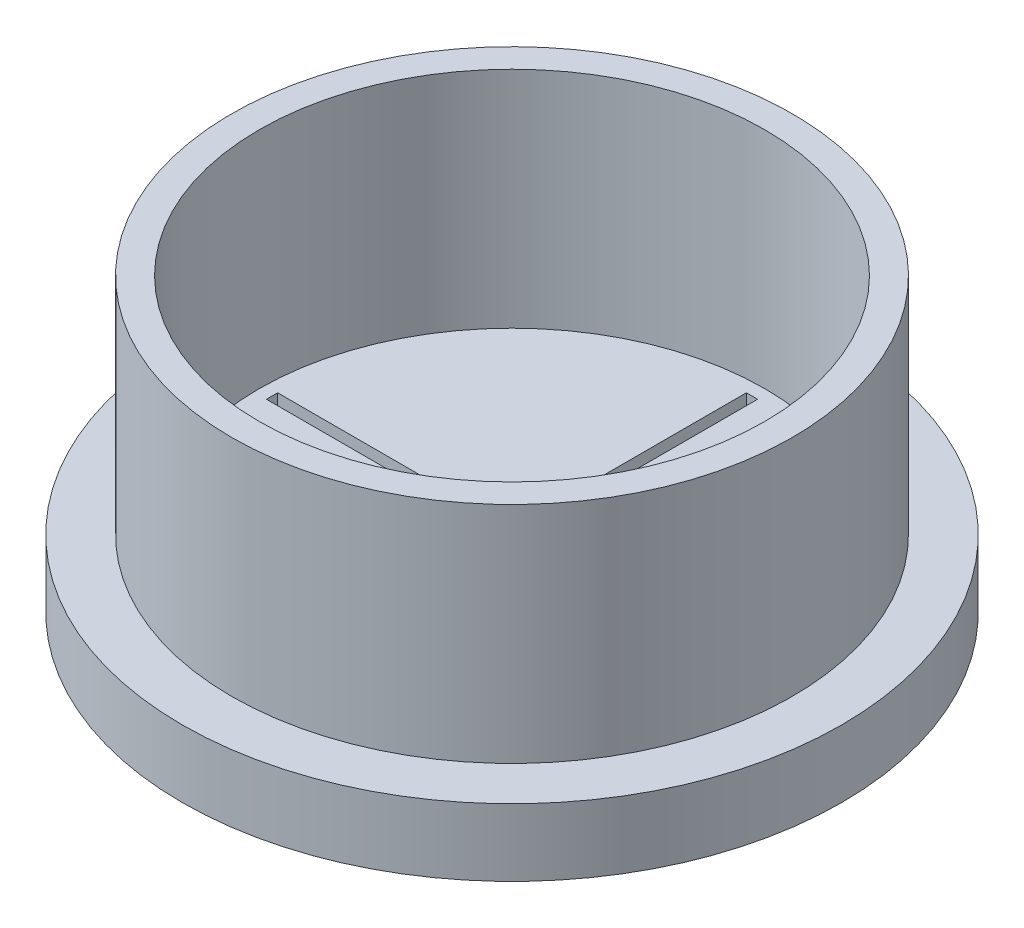
SolidWorks part; units mm, degrees
ref_plane "Front Plane" through (0, 0, 0) normal (0, 0, 1) x (1, 0, 0)
ref_plane "Top Plane" through (0, 0, 0) normal (0, 1, 0) x (1, 0, 0)
ref_plane "Right Plane" through (0, 0, 0) normal (1, 0, 0) x (0, 0, -1)
sketch "Sketch1" plane through (0, 0, 0) normal (0, 1, 0) x (1, 0, 0)
  circle A0 centre (0, 0) radius 14.7
  point P3 (0, 0)
  dimension "D1" = 29.4
extrude "Boss-Extrude1" add sketch "Sketch1" along normal blind 3
sketch "Sketch3" plane through (0, 3, 0) normal (0, 1, 0) x (1, 0, 0)
  line L1 (-10.7, 0.25) -> (10.7, 0.25)
  line L2 (-10.7, 0.25) -> (-10.7, -0.25)
  line L3 (-10.7, -0.25) -> (10.7, -0.25)
  line L4 (10.7, 0.25) -> (10.7, -0.25)
  line L5 (-10.7, 0.25) -> (10.7, -0.25) construction
  line L6 (-10.7, -0.25) -> (10.7, 0.25) construction
  point P0 (0, 0)
  dimension "D1" = 0.5
  dimension "D2" = 21.4
extrude "Cut-Extrude1" cut sketch "Sketch3" against normal blind 3 contours L3 L4 L1 L2
sketch "Sketch4" plane through (0, 3, 0) normal (0, 1, 0) x (1, 0, 0)
  line L1 (-0.25, 10.7) -> (0.25, 10.7)
  line L2 (-0.25, 10.7) -> (-0.25, -10.7)
  line L3 (-0.25, -10.7) -> (0.25, -10.7)
  line L4 (0.25, 10.7) -> (0.25, -10.7)
  line L5 (-0.25, 10.7) -> (0.25, -10.7) construction
  line L6 (-0.25, -10.7) -> (0.25, 10.7) construction
  point P0 (0, 0)
  dimension "D1" = 0.5
  dimension "D2" = 21.4
extrude "Cut-Extrude2" cut sketch "Sketch4" against normal blind 3
sketch "Sketch5" plane through (0, 3, 0) normal (0, 1, 0) x (1, 0, 0)
  circle A0 centre (0, 0) radius 12.5
  dimension "D1" = 25
extrude "Boss-Extrude3" add sketch "Sketch5" along normal blind 10
sketch "Sketch6" plane through (0, 13, 0) normal (0, 1, 0) x (1, 0, 0)
  circle A0 centre (0, 0) radius 11.27
  dimension "D1" = 22.54
extrude "Cut-Extrude3" cut sketch "Sketch6" against normal blind 10
